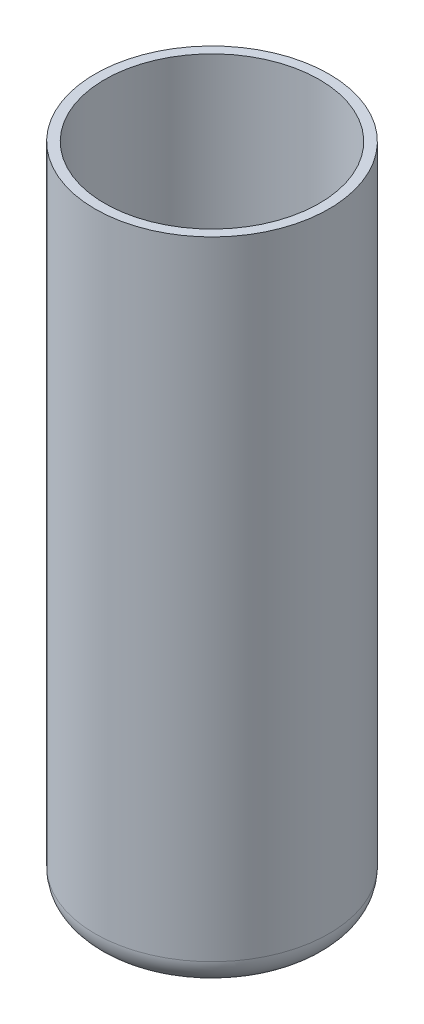
SolidWorks part; units mm, degrees
ref_plane "Front Plane" through (0, 0, 0) normal (0, 0, 1) x (1, 0, 0)
ref_plane "Top Plane" through (0, 0, 0) normal (0, 1, 0) x (1, 0, 0)
ref_plane "Right Plane" through (0, 0, 0) normal (1, 0, 0) x (0, 0, -1)
sketch "Sketch2" plane through (0, 0, 0) normal (0, 0, 1) x (1, 0, 0)
  line L0 (27.531, 168) -> (27.531, 7)
  line L1 (0, 0) -> (23, 0)
  line L2 (0, 0) -> (0, 168) construction
  line L3 (0, 168) -> (30, 168) construction
  line L4 (30, 7) -> (30, 168)
  line L5 (20, 3.6368) -> (0, 3.6368)
  line L6 (0, 0) -> (0, 3.6368)
  line L7 (27.531, 168) -> (30, 168)
  arc A0 (23, 0) -> (30, 7) centre (23, 7) ccw
  arc A1 (27.531, 7) -> (20, 3.6368) centre (18.0069, 18.2133) cw
  point P7 (30, 0)
  dimension "D3" = 7
  dimension "D1" = 30
  dimension "D2" = 168
revolve "Revolve1" add sketch "Sketch2" angle 360 about L2
